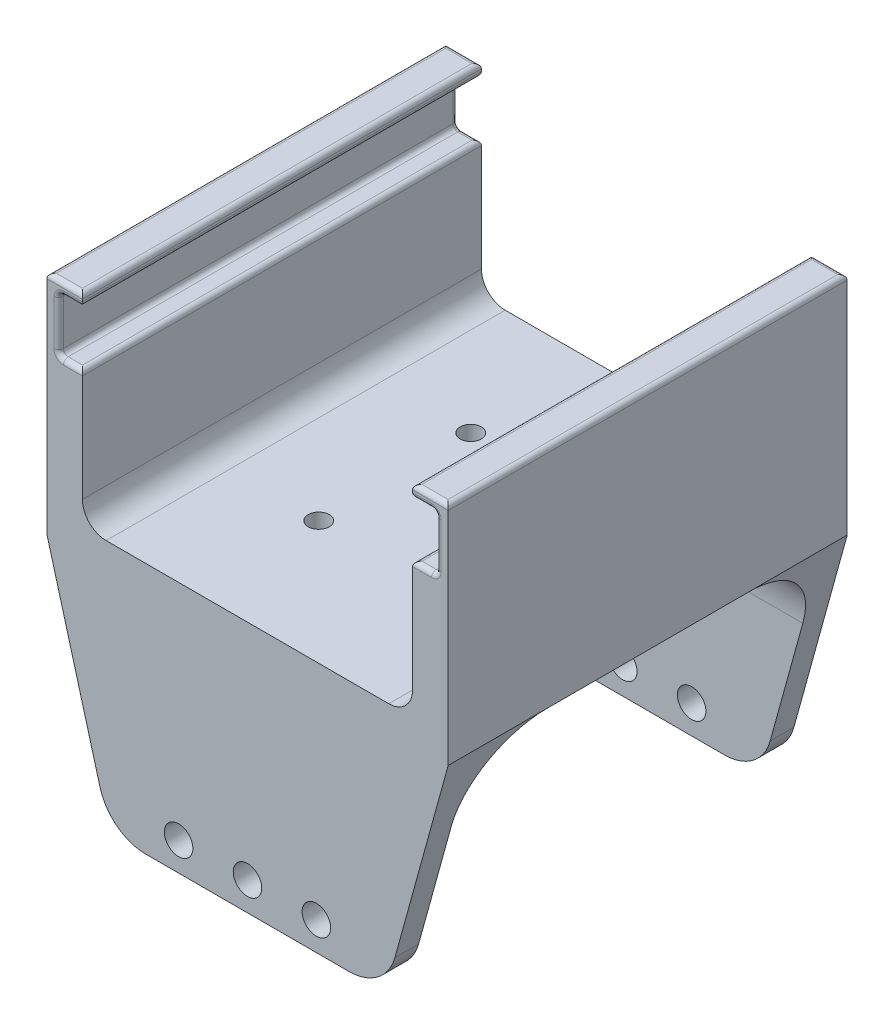
SolidWorks part; units mm, degrees
ref_plane "Front Plane" through (0, 0, 0) normal (0, 0, 1) x (1, 0, 0)
ref_plane "Top Plane" through (0, 0, 0) normal (0, 1, 0) x (1, 0, 0)
ref_plane "Right Plane" through (0, 0, 0) normal (1, 0, 0) x (0, 0, -1)
sketch "Sketch4" plane through (0, 25, 0) normal (0, 1, 0) x (1, 0, 0)
  line L0 (-19, 81) -> (39, -7) construction
  line L2 (52.25, -5) -> (-32.25, -5)
  line L3 (52.25, -5) -> (52.25, 79)
  line L4 (52.25, 79) -> (-32.25, 79)
  line L5 (-32.25, -5) -> (-32.25, 79)
  line L6 (10, 79) -> (10, -5) construction
  line L7 (52.25, 37) -> (-32.25, 37) construction
  point P4 (10, 37)
  dimension "D1" = 84
  dimension "D2" = 84.5
extrude "Boss-Extrude1" add sketch "Sketch4" along normal blind 5
sketch "Sketch5" plane through (0, 25, 0) normal (0, -1, 0) x (1, 0, 0)
  line L0 (52.25, 5) -> (52.25, -79) construction
  line L1 (-32.25, 5) -> (52.25, 5)
  line L2 (-32.25, 5) -> (-32.25, 0)
  line L3 (-32.25, 0) -> (52.25, 0)
  line L4 (52.25, 5) -> (52.25, 0)
  line L6 (-32.25, -79) -> (52.25, -79)
  line L7 (-32.25, -79) -> (-32.25, -74)
  line L8 (-32.25, -74) -> (52.25, -74)
  line L9 (52.25, -79) -> (52.25, -74)
  dimension "D1" = 5
extrude "Boss-Extrude2" add sketch "Sketch5" along normal blind 48
sketch "Sketch6" plane through (0, 25, 0) normal (0, -1, 0) x (1, 0, 0)
  circle A0 centre (-1, -21) radius 2.225
  circle A1 centre (-1, -53) radius 2.225
extrude "Cut-Extrude1" cut sketch "Sketch6" against normal blind 48
sketch "Sketch7" plane through (0, 30, 0) normal (0, 1, 0) x (1, 0, 0)
  line L0 (-32.25, -5) -> (52.25, -5) construction
  line L1 (-32.25, 79) -> (-24.75, 79)
  line L2 (-32.25, 79) -> (-32.25, -5)
  line L3 (-32.25, -5) -> (-24.75, -5)
  line L4 (-24.75, 79) -> (-24.75, -5)
  line L6 (52.25, 79) -> (44.75, 79)
  line L7 (52.25, 79) -> (52.25, -5)
  line L8 (52.25, -5) -> (44.75, -5)
  line L9 (44.75, 79) -> (44.75, -5)
  dimension "D1" = 7.5
extrude "Boss-Extrude3" add sketch "Sketch7" along normal blind 28.5
sketch "Sketch8" plane through (0, 58.5, 0) normal (0, 1, 0) x (1, 0, 0)
  line L0 (-32.25, -5) -> (-24.75, -5) construction
  line L1 (-32.25, 79) -> (-29.75, 79)
  line L2 (-32.25, 79) -> (-32.25, -5)
  line L3 (-32.25, -5) -> (-29.75, -5)
  line L4 (-29.75, 79) -> (-29.75, -5)
  line L5 (52.25, 79) -> (44.75, 79) construction
  line L6 (52.25, -5) -> (49.75, -5)
  line L7 (52.25, -5) -> (52.25, 79)
  line L8 (52.25, 79) -> (49.75, 79)
  line L9 (49.75, -5) -> (49.75, 79)
  dimension "D1" = 2.5
extrude "Boss-Extrude4" add sketch "Sketch8" along normal blind 11.5
sketch "Sketch9" plane through (0, 0, 0) normal (0, 0, -1) x (-1, 0, 0)
  circle A0 centre (-10, -17) radius 3
  circle A1 centre (-24.5, -17) radius 3
  circle A2 centre (4.5, -17) radius 3
extrude "Cut-Extrude2" cut sketch "Sketch9" against normal blind 5 and the other way blind 93
sketch "Sketch10" plane through (0, 70, 0) normal (0, 1, 0) x (1, 0, 0)
  line L1 (52.25, 79) -> (44.75, 79)
  line L2 (52.25, 79) -> (52.25, -5)
  line L3 (52.25, -5) -> (44.75, -5)
  line L4 (44.75, 79) -> (44.75, -5)
  line L5 (-32.25, 79) -> (-24.75, 79)
  line L6 (-32.25, 79) -> (-32.25, -5)
  line L7 (-32.25, -5) -> (-24.75, -5)
  line L8 (-24.75, 79) -> (-24.75, -5)
extrude "Boss-Extrude5" add sketch "Sketch10" along normal blind 2.5
fillet "Fillet1" radius 1 28 edges at (-29.75, 64.25, -79) (-29.75, 64.25, 5) (49.75, 64.25, 5) (49.75, 64.25, -79) (48.5, 72.5, 5) (44.75, 72.5, -37) (48.5, 72.5, -79) (52.25, 72.5, -37) (-28.5, 72.5, -79) (-24.75, 72.5, -37) (-28.5, 72.5, 5) (-24.75, 58.5, -37) (-27.25, 58.5, 5) (-29.75, 58.5, -37) (-27.25, 58.5, -79) (-24.75, 70, -37) (-27.25, 70, -79) (-29.75, 70, -37) (-27.25, 70, 5) (47.25, 70, -79) (44.75, 70, -37) (47.25, 70, 5) (49.75, 70, -37) (47.25, 58.5, 5) (44.75, 58.5, -37) (47.25, 58.5, -79) (49.75, 58.5, -37) (-32.25, 72.5, -37)
sketch "Sketch11" plane through (0, 0, 0) normal (0, 0, -1) x (-1, 0, 0)
  line L3 (32.25, -23) -> (-52.25, -23) construction
  line L4 (19, -23) -> (32.25, -23)
  line L5 (32.25, -23) -> (32.25, 25)
  line L6 (32.25, 25) -> (19, -23)
  line L7 (-39, -23) -> (-52.25, -23)
  line L8 (-52.25, -23) -> (-52.25, 25)
  line L9 (-52.25, 25) -> (-39, -23)
  dimension "D1" = 13.25
  dimension "D2" = 13.25
extrude "Cut-Extrude3" cut sketch "Sketch11" against normal blind 24.5 and the other way blind 88
fillet "Fillet2" radius 10 4 edges at (39, -23, 2.5) (-19, -23, 2.5) (39, -23, -76.5) (-19, -23, -76.5)
fillet "Fillet3" radius 5 2 edges at (44.75, 30, -37) (-24.75, 30, -37)
fillet "Fillet4" radius 15.75 2 edges at (10, 25, 0) (10, 25, -74)
